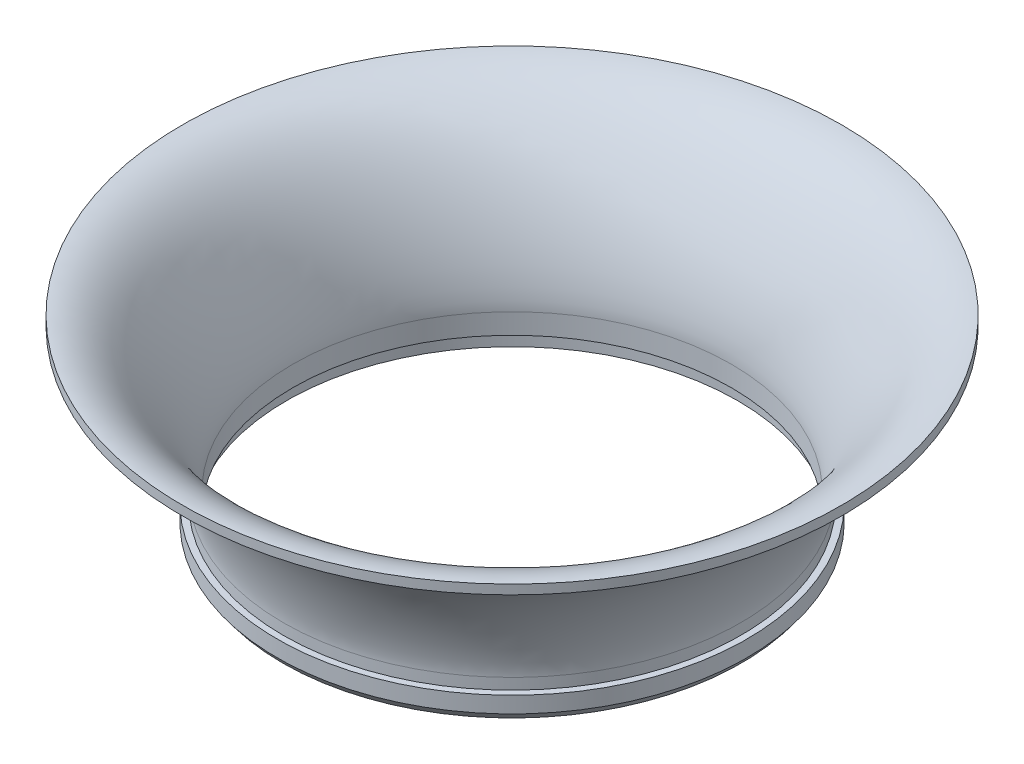
SolidWorks part; units mm, degrees
ref_plane "Front Plane" through (0, 0, 0) normal (0, 0, 1) x (1, 0, 0)
ref_plane "Top Plane" through (0, 0, 0) normal (0, 1, 0) x (1, 0, 0)
ref_plane "Right Plane" through (0, 0, 0) normal (1, 0, 0) x (0, 0, -1)
sketch "Sketch1" plane through (0, 0, 0) normal (0, 0, 1) x (1, 0, 0)
  line L0 (0, 0) -> (30.4865, 0) construction
  line L1 (0, 0) -> (0, 36.8) construction
  line L2 (0, 0) -> (-52.9, 0) construction
  line L3 (-52.9, 0) -> (-52.9, 28.4324) construction
  line L4 (-36.8, 0) -> (-36.2, 0)
  line L5 (-36.2, 0) -> (-36.2, 2.3)
  line L6 (-36.2, 2.3) -> (-35.2, 2.3)
  line L7 (-35.2, 2.3) -> (-35.2, 5.5676)
  line L8 (-35.2, 13.3529) -> (-35.2, -2.2177) construction
  line L9 (-58.3249, 30) -> (-41.4751, 30) construction
  line L10 (-37.7, 1.2) -> (-37.7, 1.2)
  line L11 (-37.7, 1.2) -> (-37.7, 3.8)
  line L12 (-37.7, 3.8) -> (-36.7, 3.8)
  line L13 (-36.7, 3.8) -> (-36.7, 5.5676)
  line L14 (-36.8, 0) -> (-37.7, 1.2)
  line L15 (-52.9, 30) -> (-52.9, 28.5)
  spline S0 degree 3 poles (-35.2, 5.5676) (-35.2, 12.0553) (-42.3688, 30) (-52.9, 30) knots 0 0 0 0 1 1 1 1
  spline S1 degree 1 poles (-36.7, 5.5676) (-52.9, 28.5) knots 0 0 1 1 construction
  spline S2 degree 3 poles (-36.7, 5.5676) (-36.7, 5.7504) (-36.7117, 6.0961) (-36.7856, 6.9449) (-36.9752, 8.1576) (-37.3571, 9.8264) (-38.0655, 12.2509) (-39.3091, 15.5371) (-41.3193, 19.5127) (-43.7807, 23.1569) (-46.6101, 26.1107) (-49.6697, 28.0381) (-51.8086, 28.5) (-52.9, 28.5) knots 0 0 0 0 0.03125 0.0625 0.125 0.1875 0.25 0.375 0.5 0.625 0.75 0.875 1 1 1 1
  dimension "D1" = 30
  dimension "D2" = 0.6
  dimension "D3" = 1.6
  dimension "D4" = 52.9
  dimension "D5" = 1.5
  dimension "D6" = 36.8
  dimension "D7" = 2.3
revolve "Revolve1" add sketch "Sketch1" angle 360 about L1
